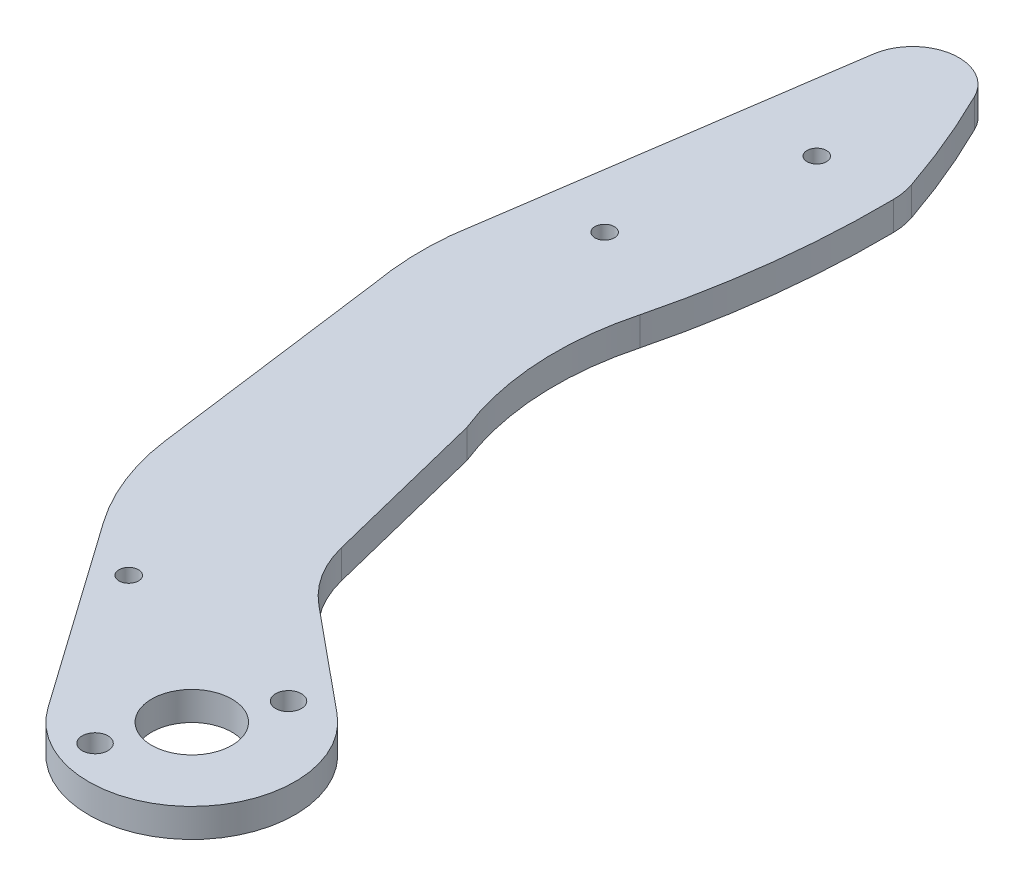
SolidWorks part; units mm, degrees
ref_plane "Front Plane" through (0, 0, 0) normal (0, 0, 1) x (1, 0, 0)
ref_plane "Top Plane" through (0, 0, 0) normal (0, 1, 0) x (1, 0, 0)
ref_plane "Right Plane" through (0, 0, 0) normal (1, 0, 0) x (0, 0, -1)
sketch "Sketch1" plane through (0, 0, 0) normal (0, 1, 0) x (1, 0, 0)
  line L42 (11.4465, 13.8917) -> (-6.607, 28.7674)
  line L43 (-13.2989, 39.3817) -> (-20.5302, 68.4972)
  line L44 (-41.4826, 160.3656) -> (-50.9327, 96.0562)
  line L45 (-50.3835, 82.3644) -> (-44.8193, 40.2497)
  line L46 (-37.8507, 22.4331) -> (-14.709, -10.3752)
  arc A148 (-22.4566, 100.5997) -> (-20.5302, 68.4972) centre (26.9938, 87.458) ccw
  arc A149 (-22.4566, 100.5997) -> (-17.768, 140.1479) centre (-171.2572, 138.2924) ccw
  arc A150 (-17.768, 140.1479) -> (-18.4178, 143.9365) centre (-30, 140) ccw
  arc A151 (-18.4178, 143.9365) -> (-26.2563, 162.7822) centre (-163.7532, 94.5401) ccw
  arc A152 (-26.2563, 162.7822) -> (-41.4826, 160.3656) centre (-33.4913, 159.1913) ccw
  arc A153 (-50.9327, 96.0562) -> (-50.3835, 82.3644) centre (0.0072, 91.2427) ccw
  circle A154 centre (0, 0) radius 7
  arc A155 (11.4465, 13.8917) -> (-14.709, -10.3752) centre (0, 0) cw
  arc A156 (-6.607, 28.7674) -> (-13.2989, 39.3817) centre (6.1114, 44.2025) cw
  arc A157 (-44.8193, 40.2497) -> (-37.8507, 22.4331) centre (-5.1639, 45.489) ccw
  circle A158 centre (-27.6733, 16.679) radius 1.7
  point P7 (-11.7063, 32.9691)
  point P11 (-43.529, 30.4833)
  dimension "D3" = 65
  dimension "D4" = 14
  dimension "D5" = 11
  dimension "D8" = 20
  dimension "D10" = 40
  dimension "D11" = 3.4
  dimension "D1" = 140
  dimension "D2" = 30
  dimension "D6" = 50
  dimension "D7" = 30
  dimension "D9" = 30
  dimension "D12" = 5
  dimension "D13" = 30
extrude "Boss-Extrude2" add sketch "Sketch1" along normal blind 5
sketch "Sketch2" plane through (0, 5, 0) normal (0, 1, 0) x (1, 0, 0)
  line L0 (11.4465, 13.8917) -> (-6.607, 28.7674) construction
  point P0 (8.4963, 16.3225)
sketch "Sketch3" plane through (0, 5, 0) normal (0, 1, 0) x (1, 0, 0)
  circle A0 centre (-31, 140) radius 1.7
  circle A1 centre (-38, 110) radius 1.7
  dimension "D1" = 3.4
  dimension "D2" = 3.4
  dimension "D3" = 30
  dimension "D4" = 110
  dimension "D5" = 38
  dimension "D6" = 7
extrude "Cut-Extrude1" cut sketch "Sketch3" against normal up to next
sketch "Sketch4" plane through (0, 5, 0) normal (0, 1, 0) x (1, 0, 0)
  point P0 (5.2512, 11.6184)
  point P1 (-5.2512, -11.6184)
  point P3 (0, 0)
  point P5 (0, 0)
  point P6 (0, 0)
hole_wizard "M4 Clearance Hole1" positions "3DSketch2" profile "Sketch6" hole size "M4" standard "ISO"
sketch3d "3DSketch2"
  point P0 (-5.2512, 5, 11.6184)
  point P2 (5.2512, 5, -11.6184)
sketch "Sketch6" plane through (-5.2512, 5, 11.6184) normal (1, 0, 0) x (0, 0, 1)
  line L0 (0, 0) -> (0, 11.4519)
  line L1 (0, 11.4519) -> (2.25, 10.1)
  line L2 (2.25, 10.1) -> (2.25, 0)
  line L5 (2.25, 0) -> (0, 0)
  line L10 (0, 11.4519) -> (-2.25, 10.1) construction
  line L11 (0, -6.35) -> (0, 107.95) construction
  dimension "Hole Dia." = 4.5
  dimension "Hole Depth" = 10.1
  dimension "Drill Angle" = 118
